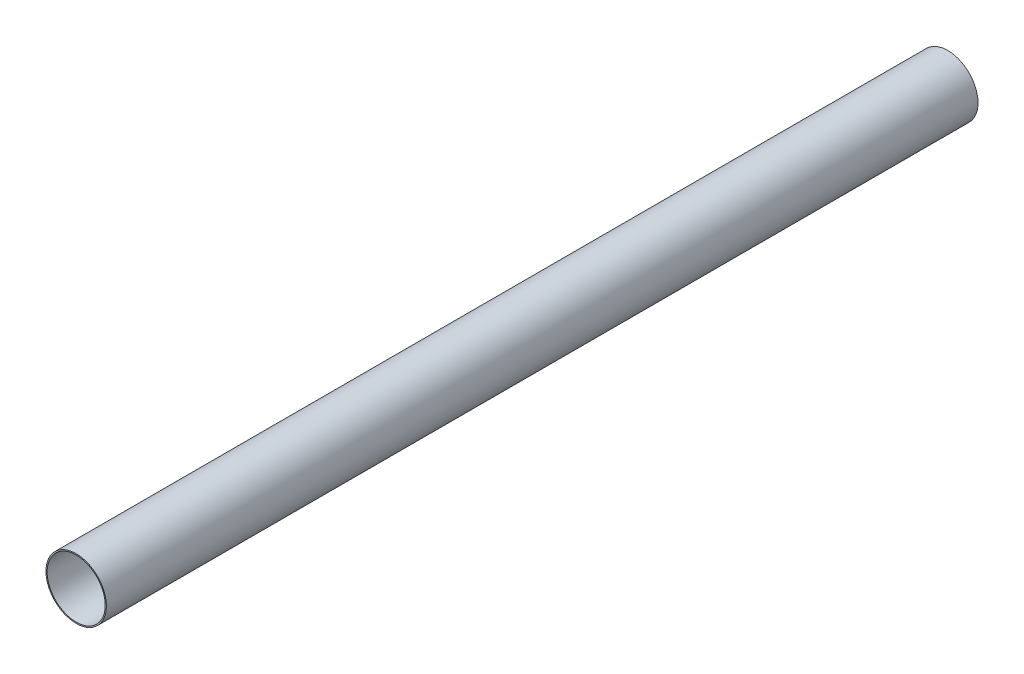
SolidWorks part; units mm, degrees
ref_plane "Front Plane" through (0, 0, 0) normal (0, 0, 1) x (1, 0, 0)
ref_plane "Top Plane" through (0, 0, 0) normal (0, 1, 0) x (1, 0, 0)
ref_plane "Right Plane" through (0, 0, 0) normal (1, 0, 0) x (0, 0, -1)
sketch "Sketch1" plane through (0, 0, 0) normal (0, 0, 1) x (1, 0, 0)
  circle A0 centre (0, 0) radius 38.1
  circle A1 centre (0, 0) radius 39.624
  dimension "D1" = 76.2
  dimension "D2" = 79.248
extrude "Boss-Extrude1" add sketch "Sketch1" along normal blind 1143
